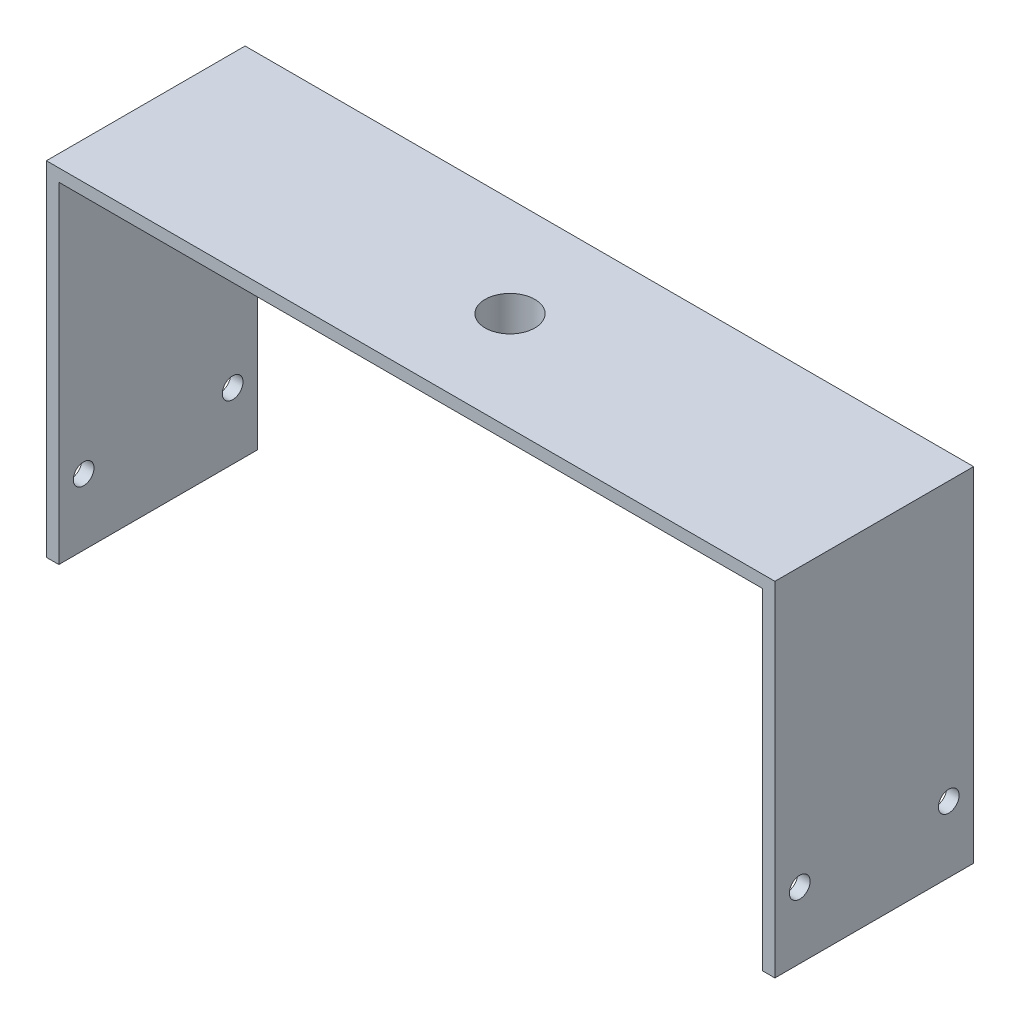
SolidWorks part; units mm, degrees
ref_plane "Front Plane" through (0, 0, 0) normal (0, 0, 1) x (1, 0, 0)
ref_plane "Top Plane" through (0, 0, 0) normal (0, 1, 0) x (1, 0, 0)
ref_plane "Right Plane" through (0, 0, 0) normal (1, 0, 0) x (0, 0, -1)
sketch "Sketch1" plane through (0, 0, 0) normal (0, 0, 1) x (1, 0, 0)
  line L0 (-22.3718, -30.4078) -> (-20.8718, -30.4078)
  line L2 (65.6282, -30.4078) -> (65.6282, 11.0922)
  line L3 (65.6282, 11.0922) -> (-22.3718, 11.0922)
  line L4 (-22.3718, -30.4078) -> (-22.3718, 11.0922)
  line L6 (65.6282, 11.0922) -> (56.7533, 9.5922) construction
  line L8 (64.1282, -30.4078) -> (64.1282, 9.5922)
  line L9 (64.1282, 9.5922) -> (-20.8718, 9.5922)
  line L10 (-20.8718, -30.4078) -> (-20.8718, 9.5922)
  line L12 (21.6282, -10.4078) -> (21.3016, -10.5615) construction
  line L13 (64.1282, -30.4078) -> (65.6282, -30.4078)
  line L14 (-19.3464, 9.5922) -> (-22.3718, 11.0922) construction
  line L16 (-20.8718, -3.5276) -> (-22.3718, -3.7812) construction
  point P0 (0, 0)
  point P6 (21.6282, -10.4078)
  dimension "D1" = 1.5
  dimension "D2" = 1.5
  dimension "D3" = 85
  dimension "D4" = 1.5
extrude "Boss-Extrude1" add sketch "Sketch1" along normal blind 24
sketch "Sketch2" plane through (-22.3718, 0, 0) normal (-1, 0, 0) x (0, 0, 1)
  line L0 (12, -30.4078) -> (12, 11.0922) construction
  line L1 (24, -30.4078) -> (0, -30.4078) construction
  line L2 (24, 11.0922) -> (0, 11.0922) construction
  circle A0 centre (3, -22.4078) radius 1.25
  circle A1 centre (21, -22.4078) radius 1.25
  dimension "D1" = 18
  dimension "D2" = 2.5
  dimension "D3" = 8
extrude "Cut-Extrude1" cut sketch "Sketch2" against normal blind 90
sketch "Sketch3" plane through (0, 11.0922, 0) normal (0, 1, 0) x (1, 0, 0)
  line L0 (-22.3718, -12) -> (65.6282, -12) construction
  line L1 (-22.3718, -24) -> (-22.3718, 0) construction
  line L2 (65.6282, -24) -> (65.6282, 0) construction
  circle A0 centre (21.6282, -12) radius 3
  dimension "D1" = 6
extrude "Cut-Extrude2" cut sketch "Sketch3" against normal up to next
sketch "Sketch4" plane through (0, 9.5922, 0) normal (0, -1, 0) x (1, 0, 0)
  line L0 (-20.8718, 24) -> (64.1282, 24) construction
  line L1 (18.6282, 6.8038) -> (24.6282, 6.8038)
  line L2 (24.6282, 6.8038) -> (27.6282, 12)
  line L3 (27.6282, 12) -> (24.6282, 17.1962)
  line L4 (24.6282, 17.1962) -> (18.6282, 17.1962)
  line L5 (18.6282, 17.1962) -> (15.6282, 12)
  line L6 (15.6282, 12) -> (18.6282, 6.8038)
  circle A0 centre (21.6282, 12) radius 5.1962 construction
  circle A1 centre (21.6282, 12) radius 3
  dimension "D1" = 6
extrude "Boss-Extrude2" add sketch "Sketch4" along normal blind 5
